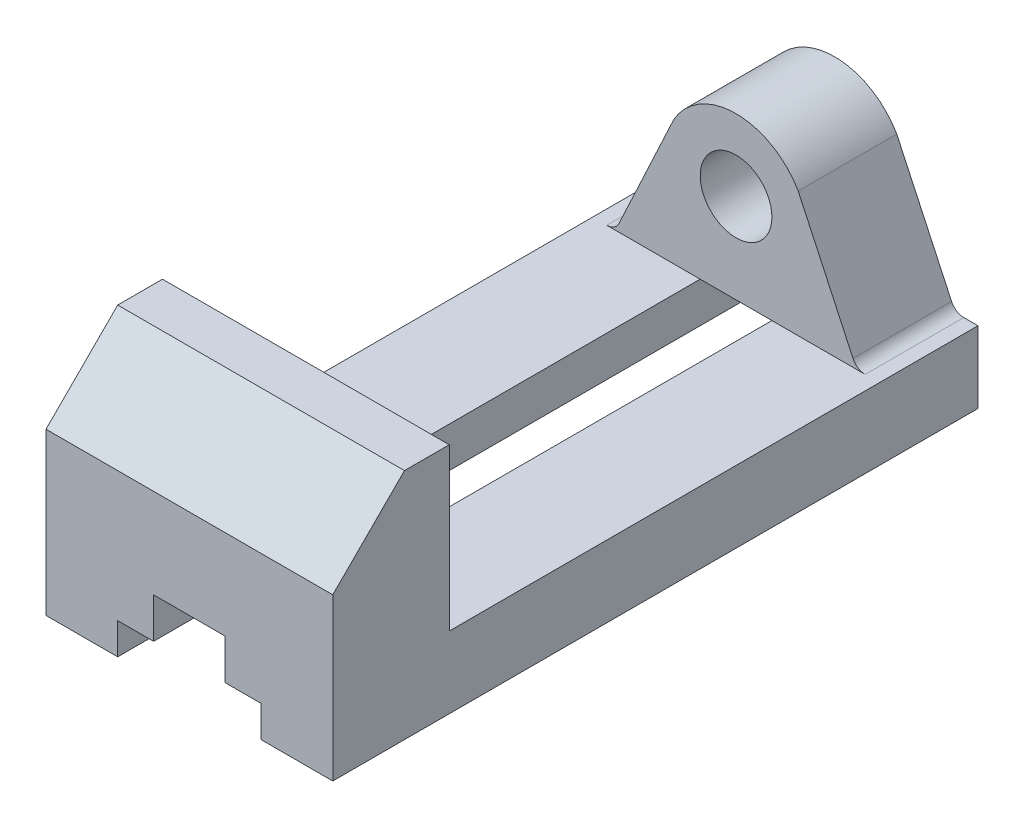
SolidWorks part; units mm, degrees
material "Gray Cast Iron"
ref_plane "Front Plane" through (0, 0, 0) normal (0, 0, 1) x (1, 0, 0)
ref_plane "Top Plane" through (0, 0, 0) normal (0, 1, 0) x (1, 0, 0)
ref_plane "Right Plane" through (0, 0, 0) normal (1, 0, 0) x (0, 0, -1)
sketch "Sketch1" plane through (0, 0, 0) normal (1, 0, 0) x (0, 0, -1)
  line L0 (0, 0) -> (0, 16)
  line L1 (0, 16) -> (-118, 16)
  line L2 (-118, 16) -> (-118, 52)
  line L3 (-118, 52) -> (-128, 52)
  line L4 (-128, 52) -> (-144, 36)
  line L5 (-144, 36) -> (-144, 0)
  line L6 (0, 0) -> (-144, 0)
  dimension "D1" = 16
  dimension "D2" = 144
  dimension "D3" = 36
  dimension "D4" = 10
  dimension "D5" = 16
  dimension "D6" = 16
extrude "Boss-Extrude1" add sketch "Sketch1" along normal mid plane 64 contours L6 L5 L4 L3 L2 L1 L0
sketch "Sketch3" plane through (0, 0, 0) normal (0, 0, 1) x (1, 0, 0)
  line L0 (0, -21.6296) -> (0, 53.6296) construction
  line L2 (26.9157, 16) -> (13.8705, 43.9756)
  line L3 (32, 16) -> (-32, 16) construction
  line L4 (32, 0) -> (-32, 0) construction
  line L6 (-26.9157, 16) -> (-13.8705, 43.9756)
  line L7 (26.9157, 16) -> (-26.9157, 16)
  arc A0 (13.8705, 43.9756) -> (-13.8705, 43.9756) centre (0, 36) ccw
  circle A1 centre (0, 36) radius 8
  point P3 (0, 16)
  dimension "D4" = 32
  dimension "D5" = 16
  dimension "D1" = 25
  dimension "D2" = 13.8705
  dimension "D6" = 36
extrude "Boss-Extrude2" add sketch "Sketch3" along normal blind 22
sketch "Sketch7" plane through (0, 0, 0) normal (0, 1, 0) x (1, 0, 0)
  line L0 (32, 0) -> (-32, 0) construction
  line L1 (-32, 0) -> (-32, -144) construction
  circle A0 centre (-22, -38) radius 3
  dimension "D3" = 6
  dimension "D1" = 38
  dimension "D2" = 10
hole_wizard "M6x1.0 Tapped Hole2" positions "Sketch8" profile "Sketch9" tap size "M6x1.0" standard "ANSI Metric"
sketch "Sketch8" plane through (0, 0, 0) normal (0, -1, 0) x (-1, 0, 0)
  line L0 (-32, 0) -> (-32, -144) construction
  line L1 (-32, 0) -> (32, 0) construction
  line L2 (80.9048, -38) -> (-36.9048, -38) construction
  line L3 (22, -108) -> (-35.1211, -108) construction
  point P0 (22, -38)
  point P3 (22, -108)
  point P5 (-22, -108)
  point P7 (-22, -38)
  point P280 (22, -38)
  dimension "D1" = 70
  dimension "D2" = 10
  dimension "D3" = 38
  dimension "D4" = 70
  dimension "D5" = 10
  dimension "D6" = 44
sketch "Sketch9" plane through (-22, 0, 38) normal (1, 0, 0) x (0, 0, -1)
  line L0 (0, 0) -> (0, 11.5022)
  line L1 (0, 11.5022) -> (2.5, 10)
  line L2 (2.5, 10) -> (2.5, 0.4405)
  line L3 (2.5, 0.4405) -> (3.025, 0)
  line L5 (3.025, 0) -> (0, 0)
  line L6 (-2.5, 0.4405) -> (-3.025, 0) construction
  line L10 (0, 11.5022) -> (-2.5, 10) construction
  line L11 (0, -6.35) -> (0, 107.95) construction
  dimension "Tap Drill Dia." = 5
  dimension "Tap Drill Depth" = 10
  dimension "Near C'Sink Dia." = 6.05
  dimension "Near C'Sink Angle" = 100
  dimension "Drill Angle" = 118
cosmetic thread "Hole Thread3" parameters "D1"=6, "D2"=6
cosmetic thread "Hole Thread4" parameters "D1"=6, "D2"=6
cosmetic thread "Hole Thread5" parameters "D1"=6, "D2"=6
cosmetic thread "Hole Thread7" parameters "D1"=6, "D2"=6
sketch "Sketch11" plane through (0, 0, 0) normal (0, 0, 1) x (1, 0, 0)
  line L0 (0, 0) -> (0, 38.6236) construction
  line L1 (-16, 0) -> (-16, 7)
  line L2 (32, 0) -> (-32, 0) construction
  line L3 (-16, 7) -> (-8, 7)
  line L4 (-8, 7) -> (-8, 16)
  line L5 (-8, 16) -> (8, 16)
  line L6 (16, 0) -> (16, 7)
  line L7 (16, 7) -> (8, 7)
  line L8 (8, 7) -> (8, 16)
  line L9 (-16, 0) -> (-16, -2.3339)
  line L10 (-16, -2.3339) -> (16, -2.3339)
  line L11 (16, -2.3339) -> (16, 0)
  point P14 (0, 16)
  dimension "D1" = 7
  dimension "D2" = 8
  dimension "D3" = 16
  dimension "D4" = 16
  dimension "D5" = 2.3339
extrude "Cut-Extrude3" cut sketch "Sketch11" along normal through all
fillet "Fillet1" radius 3 2 edges at (-26.9157, 16, 11) (26.9157, 16, 11)
